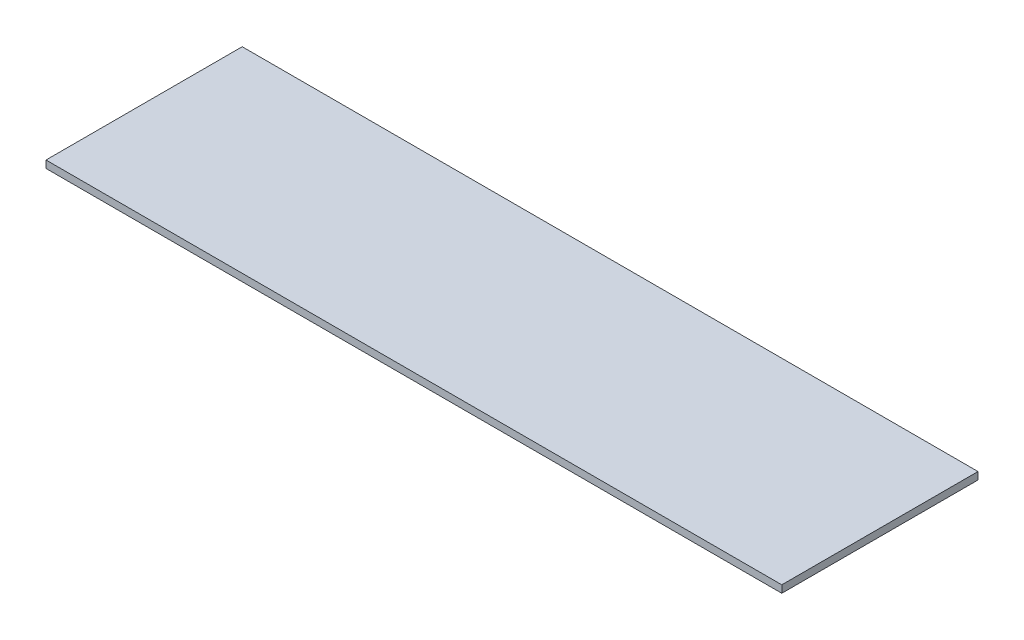
SolidWorks part; units mm, degrees
ref_plane "Front Plane" through (0, 0, 0) normal (0, 0, 1) x (1, 0, 0)
ref_plane "Top Plane" through (0, 0, 0) normal (0, 1, 0) x (1, 0, 0)
ref_plane "Right Plane" through (0, 0, 0) normal (1, 0, 0) x (0, 0, -1)
sketch "Sketch1" plane through (0, 0, 0) normal (0, 1, 0) x (1, 0, 0)
  line L1 (-150, -40) -> (150, -40)
  line L2 (-150, -40) -> (-150, 40)
  line L3 (-150, 40) -> (150, 40)
  line L4 (150, -40) -> (150, 40)
  line L5 (-150, -40) -> (150, 40) construction
  line L6 (-150, 40) -> (150, -40) construction
  point P0 (0, 0)
  dimension "D1" = 300
  dimension "D2" = 80
extrude "Boss-Extrude1" add sketch "Sketch1" along normal blind 3
